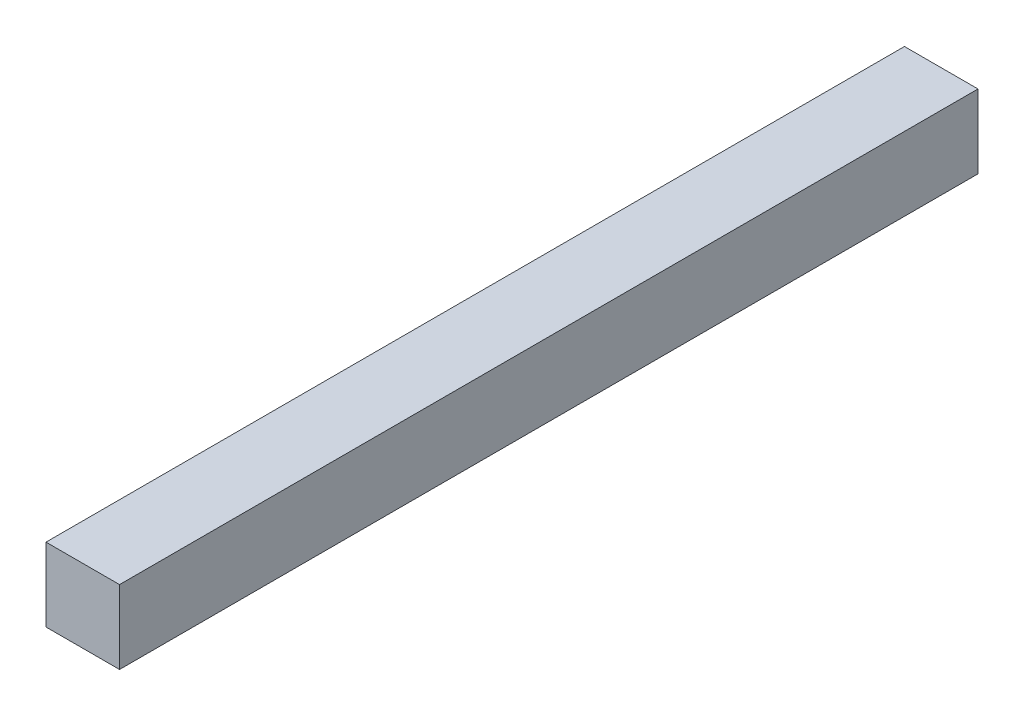
SolidWorks part; units mm, degrees
ref_plane "前视基准面" through (0, 0, 0) normal (0, 0, 1) x (1, 0, 0)
ref_plane "上视基准面" through (0, 0, 0) normal (0, 1, 0) x (1, 0, 0)
ref_plane "右视基准面" through (0, 0, 0) normal (1, 0, 0) x (0, 0, -1)
sketch "草图1" plane through (0, 0, 0) normal (0, 0, 1) x (1, 0, 0)
  line L1 (-15, 15) -> (15, 15)
  line L2 (-15, 15) -> (-15, -15)
  line L3 (-15, -15) -> (15, -15)
  line L4 (15, 15) -> (15, -15)
  line L5 (-15, 15) -> (15, -15) construction
  line L6 (-15, -15) -> (15, 15) construction
  point P0 (0, 0)
  dimension "D1" = 30
  dimension "D2" = 30
extrude "凸台-拉伸1" add sketch "草图1" along normal mid plane 350.2
